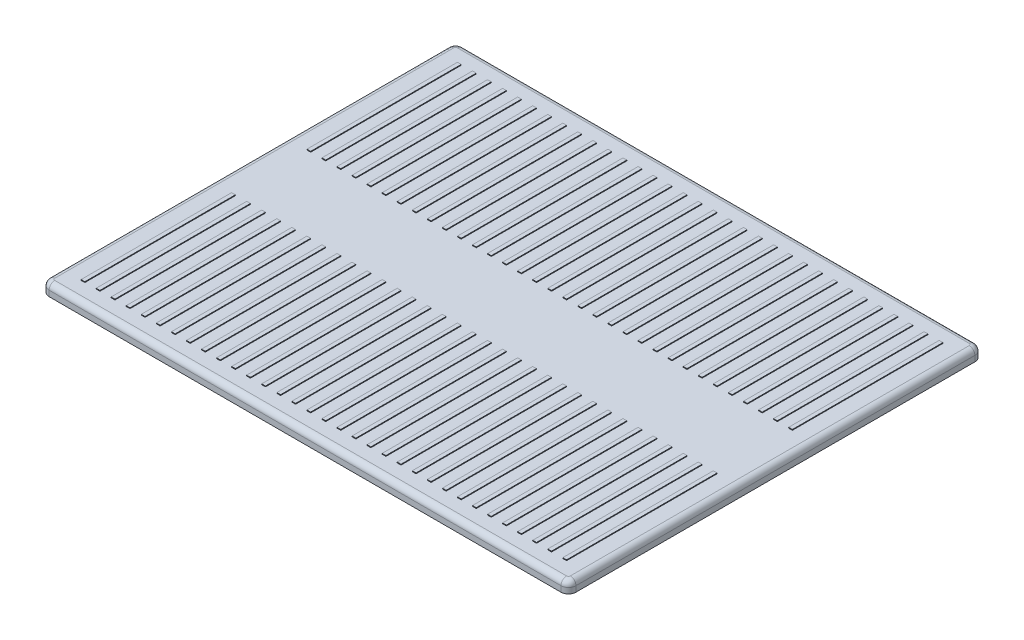
SolidWorks part; units mm, degrees
ref_plane "Front Plane" through (0, 0, 0) normal (0, 0, 1) x (1, 0, 0)
ref_plane "Top Plane" through (0, 0, 0) normal (0, 1, 0) x (1, 0, 0)
ref_plane "Right Plane" through (0, 0, 0) normal (1, 0, 0) x (0, 0, -1)
sketch "Sketch1" plane through (0, 0, 0) normal (0, 1, 0) x (1, 0, 0)
  line L1 (-34, -27.5) -> (34, -27.5)
  line L2 (-35, -26.5) -> (-35, 26.5)
  line L3 (-34, 27.5) -> (34, 27.5)
  line L4 (35, -26.5) -> (35, 26.5)
  line L5 (-35, -27.5) -> (35, 27.5) construction
  line L6 (-35, 27.5) -> (35, -27.5) construction
  arc A0 (-34, -27.5) -> (-35, -26.5) centre (-34, -26.5) cw
  arc A1 (34, -27.5) -> (35, -26.5) centre (34, -26.5) ccw
  arc A2 (34, 27.5) -> (35, 26.5) centre (34, 26.5) cw
  arc A3 (-35, 26.5) -> (-34, 27.5) centre (-34, 26.5) cw
  point P0 (0, 0)
  dimension "D3" = 1
  dimension "D1" = 70
  dimension "D2" = 55
extrude "Boss-Extrude1" add sketch "Sketch1" along normal blind 1.5
fillet "Fillet1" radius 0.75 8 edges at (-34.7071, 1.5, 27.2071) (-35, 1.5, 0) (-34.7071, 1.5, -27.2071) (0, 1.5, -27.5) (34.7071, 1.5, -27.2071) (35, 1.5, 0) (34.7071, 1.5, 27.2071) (0, 1.5, 27.5)
sketch "Sketch2" plane through (0, 1.5, 0) normal (0, 1, 0) x (1, 0, 0)
  line L1 (-0.25, 25) -> (0.25, 25)
  line L2 (-0.25, 25) -> (-0.25, 5)
  line L3 (-0.25, 5) -> (0.25, 5)
  line L4 (0.25, 25) -> (0.25, 5)
  line L5 (-0.25, 25) -> (0.25, 5) construction
  line L6 (-0.25, 5) -> (0.25, 25) construction
  point P0 (0, 15)
  point P5 (0, 0)
  dimension "D1" = 20
  dimension "D2" = 0.5
  dimension "D3" = 15
extrude "Boss-Extrude2" add sketch "Sketch2" along normal blind 0.1
pattern_linear "LPattern1" count 17 spacing 2 along (1, 0, 0) count 17 spacing 2 along (-1, 0, 0) of "Boss-Extrude2"
mirror "Mirror1" about plane through (0, 0, 0) normal (0, 0, 1) of "LPattern1", "Boss-Extrude2"
